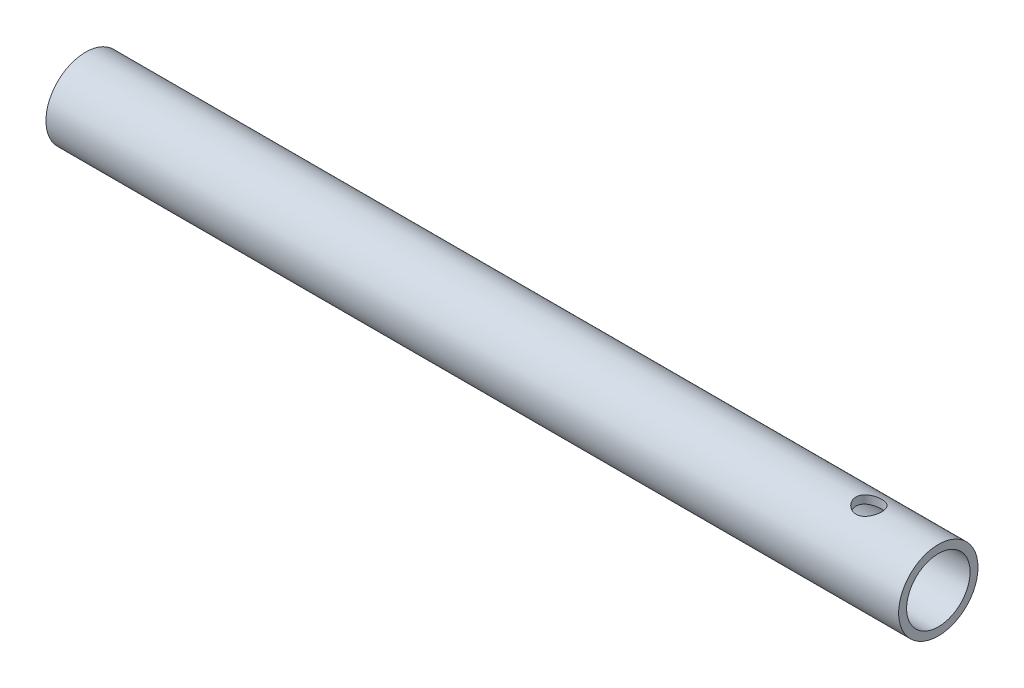
SolidWorks part; units mm, degrees
ref_plane "Front Plane" through (0, 0, 0) normal (0, 0, 1) x (1, 0, 0)
ref_plane "Top Plane" through (0, 0, 0) normal (0, 1, 0) x (1, 0, 0)
ref_plane "Right Plane" through (0, 0, 0) normal (1, 0, 0) x (0, 0, -1)
sketch "Sketch1" plane through (0, 0, 0) normal (1, 0, 0) x (0, 0, -1)
  circle A0 centre (0, 0) radius 20
  circle A1 centre (0, 0) radius 16
  dimension "D1" = 40
  dimension "D2" = 32
extrude "Boss-Extrude1" add sketch "Sketch1" against normal blind 430
ref_plane "Plane1" through (0, 50, 0) normal (0, 1, 0) x (1, 0, 0)
sketch "Sketch2" plane through (0, 0, 0) normal (0, 1, 0) x (1, 0, 0)
  line L0 (41.3741, 0) -> (-150.5723, 0) construction
  line L1 (0, -16) -> (0, 16) construction
  circle A0 centre (-35, 0) radius 6.5
  point P7 (0, 0)
  dimension "D2" = 13
  dimension "D1" = 35
extrude "Cut-Extrude1" cut sketch "Sketch2" against normal mid plane 57 contours A0
